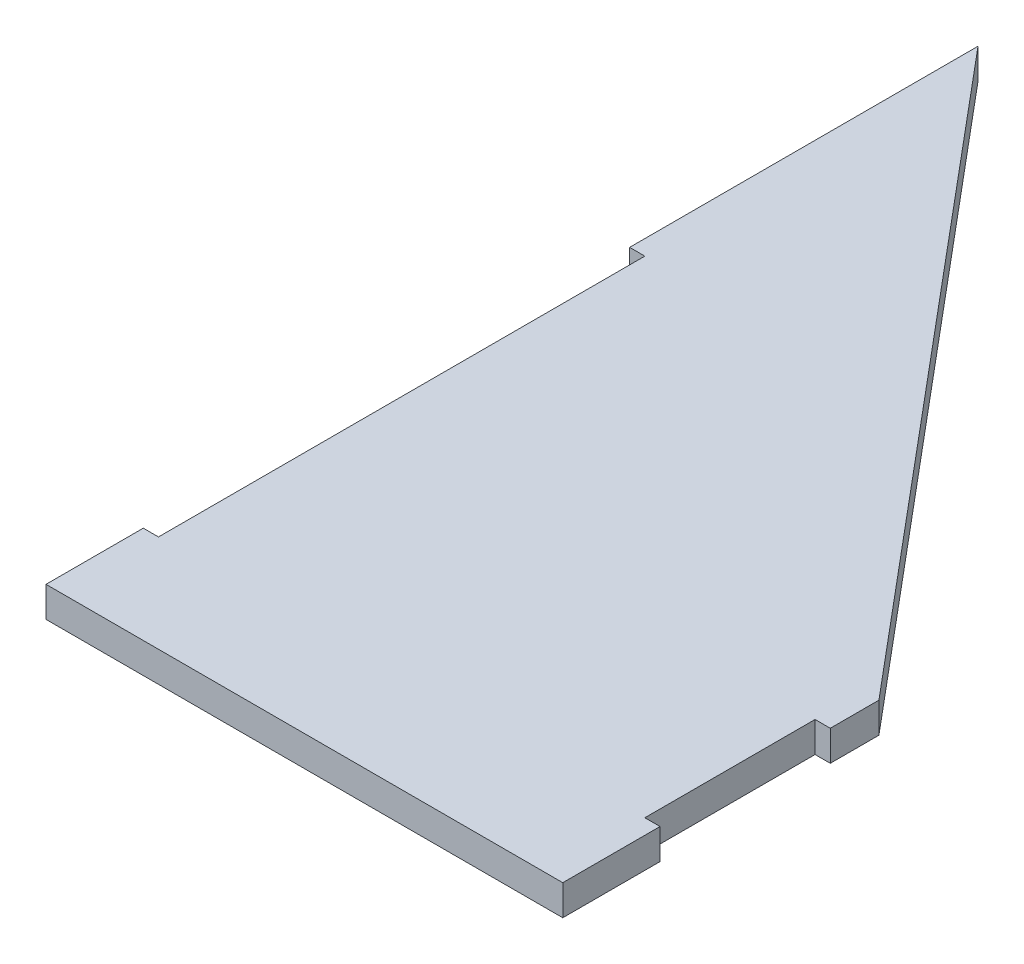
SolidWorks part; units mm, degrees
material "AISI 4130 Steel, annealed at 865C"
ref_plane "X-Y Datum" through (0, 0, 0) normal (0, 0, 1) x (1, 0, 0)
ref_plane "X-Z Datum" through (0, 0, 0) normal (0, 1, 0) x (1, 0, 0)
ref_plane "Y-Z Datum" through (0, 0, 0) normal (1, 0, 0) x (0, 0, -1)
sketch "Sketch1" plane through (0, 0, 0) normal (0, 1, 0) x (1, 0, 0)
  line L0 (-13.4938, -8.255) -> (-13.4938, -3.175) construction
  line L1 (-13.4938, -8.255) -> (13.4937, -8.255)
  line L2 (-13.4938, -8.255) -> (-13.4938, 8.255)
  line L3 (-13.4938, 8.255) -> (13.4937, 8.255)
  line L4 (13.4937, -8.255) -> (13.4937, 8.255)
  line L5 (-13.4938, -8.255) -> (13.4937, 8.255) construction
  line L6 (-13.4938, 8.255) -> (13.4937, -8.255) construction
  line L7 (0, -43.0151) -> (0, 43.0151) construction
  line L8 (-13.4938, -3.175) -> (-12.7, -3.175)
  line L9 (-13.4938, -3.175) -> (-13.4938, 22.225)
  line L10 (-13.4938, 22.225) -> (-12.7, 22.225)
  line L11 (-12.7, -3.175) -> (-12.7, 22.225)
  line L12 (13.4938, -3.175) -> (12.7, -3.175)
  line L13 (12.7, -3.175) -> (12.7, 5.715)
  line L14 (13.4938, 5.715) -> (12.7, 5.715)
  line L15 (-13.4938, 8.255) -> (-13.4938, 40.4175)
  line L16 (-13.4938, 40.4175) -> (13.4937, 8.255)
  point P1 (0, 0)
  dimension "D1" = 16.51
  dimension "D2" = 26.9875
  dimension "D3" = 5.08
  dimension "D4" = 0.7937
  dimension "D5" = 25.4
  dimension "D6" = 50
  dimension "D7" = 8.89
extrude "Boss-Extrude1" add sketch "Sketch1" along normal blind 1.5875 contours L14 L4 L3 L2 L10 L11 L8 L1 L12 L13 | L16 L15 L3
